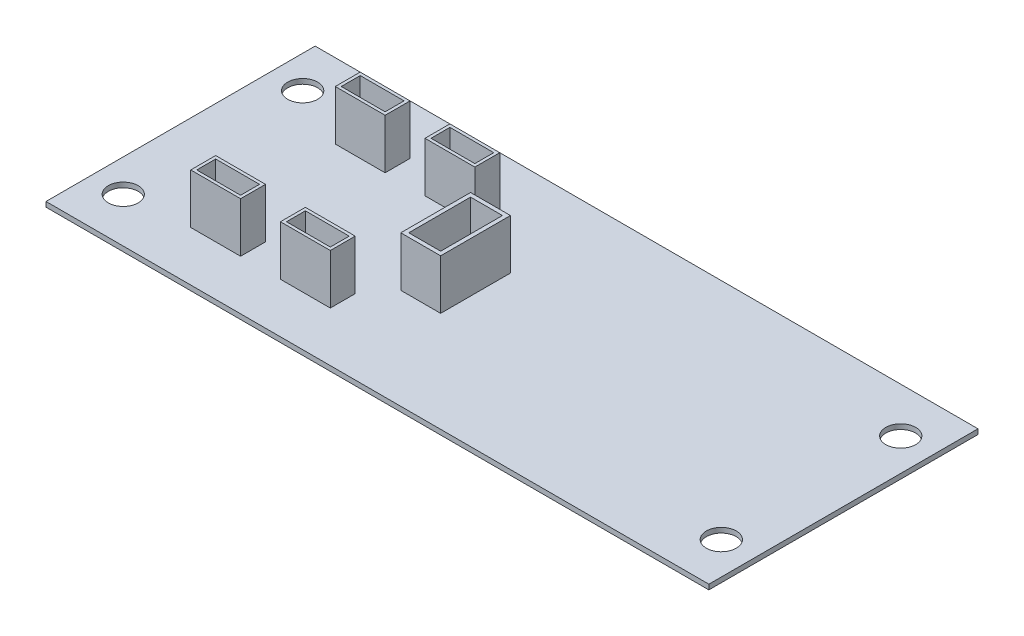
SolidWorks part; units mm, degrees
ref_plane "Front Plane" through (0, 0, 0) normal (0, 0, 1) x (1, 0, 0)
ref_plane "Top Plane" through (0, 0, 0) normal (0, 1, 0) x (1, 0, 0)
ref_plane "Right Plane" through (0, 0, 0) normal (1, 0, 0) x (0, 0, -1)
sketch "Sketch1" plane through (0, 0, 0) normal (0, 1, 0) x (1, 0, 0)
  line L1 (-33.25, 13.5) -> (33.25, 13.5)
  line L2 (-33.25, 13.5) -> (-33.25, -13.5)
  line L3 (-33.25, -13.5) -> (33.25, -13.5)
  line L4 (33.25, 13.5) -> (33.25, -13.5)
  line L5 (-33.25, 13.5) -> (33.25, -13.5) construction
  line L6 (-33.25, -13.5) -> (33.25, 13.5) construction
  circle A0 centre (-30, 9) radius 1.5
  circle A1 centre (-30, -9) radius 1.5
  circle A2 centre (30, 9) radius 1.5
  circle A3 centre (30, -9) radius 1.5
  point P0 (0, 0)
  dimension "D7" = 3
  dimension "D8" = 3
  dimension "D9" = 3
  dimension "D10" = 3
  dimension "D1" = 27
  dimension "D2" = 66.5
  dimension "D3" = 18
  dimension "D4" = 3.25
  dimension "D5" = 60
  dimension "D6" = 4.5
  dimension "D11" = 18
extrude "Boss-Extrude1" add sketch "Sketch1" along normal blind 0.5
sketch "Sketch2" plane through (0, 0.5, 0) normal (0, 1, 0) x (1, 0, 0)
  line L0 (33.25, 13.5) -> (-33.25, 13.5) construction
  line L1 (-23.7289, 6) -> (-9.7289, 6) construction
  line L2 (-23.7289, 6) -> (-23.7289, -6) construction
  line L3 (-23.7289, -6) -> (-9.7289, -6) construction
  line L4 (-9.7289, 6) -> (-9.7289, -6) construction
  line L6 (-23.7289, 6) -> (-23.7289, 8.5)
  line L7 (-23.7289, 8.5) -> (-18.7289, 8.5)
  line L8 (-18.7289, 8.5) -> (-18.7289, 6)
  line L9 (-18.7289, 6) -> (-23.7289, 6)
  line L10 (-23.4289, 8.2) -> (-19.0289, 8.2)
  line L11 (-19.0289, 8.2) -> (-19.0289, 6.3)
  line L12 (-19.0289, 6.3) -> (-23.4289, 6.3)
  line L13 (-23.4289, 6.3) -> (-23.4289, 8.2)
  line L14 (-16.7289, 6) -> (-16.7289, -6) construction
  line L15 (-14.4289, 6.3) -> (-10.0289, 6.3)
  line L16 (-10.0289, 8.2) -> (-14.4289, 8.2)
  line L17 (-9.7289, 8.5) -> (-14.7289, 8.5)
  line L18 (-14.7289, 6) -> (-9.7289, 6)
  line L19 (-9.7289, 6) -> (-9.7289, 8.5)
  line L20 (-10.0289, 6.3) -> (-10.0289, 8.2)
  line L21 (-14.4289, 8.2) -> (-14.4289, 6.3)
  line L22 (-14.7289, 8.5) -> (-14.7289, 6)
  line L23 (-23.7289, 0) -> (-9.7289, 0) construction
  line L24 (-23.7289, -6) -> (-9.7289, -6) construction
  line L25 (-14.7289, -8.5) -> (-14.7289, -6)
  line L26 (-14.4289, -8.2) -> (-14.4289, -6.3)
  line L27 (-10.0289, -6.3) -> (-10.0289, -8.2)
  line L28 (-9.7289, -6) -> (-9.7289, -8.5)
  line L29 (-14.7289, -6) -> (-9.7289, -6)
  line L30 (-9.7289, -8.5) -> (-14.7289, -8.5)
  line L31 (-10.0289, -8.2) -> (-14.4289, -8.2)
  line L32 (-14.4289, -6.3) -> (-10.0289, -6.3)
  line L33 (-23.4289, -6.3) -> (-23.4289, -8.2)
  line L34 (-19.0289, -6.3) -> (-23.4289, -6.3)
  line L35 (-19.0289, -8.2) -> (-19.0289, -6.3)
  line L36 (-23.4289, -8.2) -> (-19.0289, -8.2)
  line L37 (-18.7289, -6) -> (-23.7289, -6)
  line L38 (-18.7289, -8.5) -> (-18.7289, -6)
  line L39 (-23.7289, -8.5) -> (-18.7289, -8.5)
  line L40 (-23.7289, -6) -> (-23.7289, -8.5)
  point P0 (-9.7289, 0)
  dimension "D1" = 14
  dimension "D2" = 12
  dimension "D3" = 13.5
  dimension "D4" = 2.5
  dimension "D5" = 5
  dimension "D6" = 0.3
extrude "Boss-Extrude2" add sketch "Sketch2" along normal blind 5
sketch "Sketch4" plane through (0, 0.5, 0) normal (0, 1, 0) x (1, 0, 0)
  line L0 (-4.1324, 3.1744) -> (-4.1324, -3.0256)
  line L1 (-7.7324, 3.5744) -> (-3.7324, 3.5744)
  line L2 (-7.7324, 3.5744) -> (-7.7324, -3.4256)
  line L3 (-7.7324, -3.4256) -> (-3.7324, -3.4256)
  line L4 (-3.7324, 3.5744) -> (-3.7324, -3.4256)
  line L5 (-7.7324, 3.5744) -> (-3.7324, -3.4256) construction
  line L6 (-7.7324, -3.4256) -> (-3.7324, 3.5744) construction
  line L7 (-7.3324, -3.0256) -> (-4.1324, -3.0256)
  line L8 (-7.3324, 3.1744) -> (-7.3324, -3.0256)
  line L9 (-7.3324, 3.1744) -> (-4.1324, 3.1744)
  point P0 (-5.7324, 0.0744)
  dimension "D1" = 7
  dimension "D2" = 4
  dimension "D3" = 0.4
extrude "Boss-Extrude3" add sketch "Sketch4" along normal blind 5
